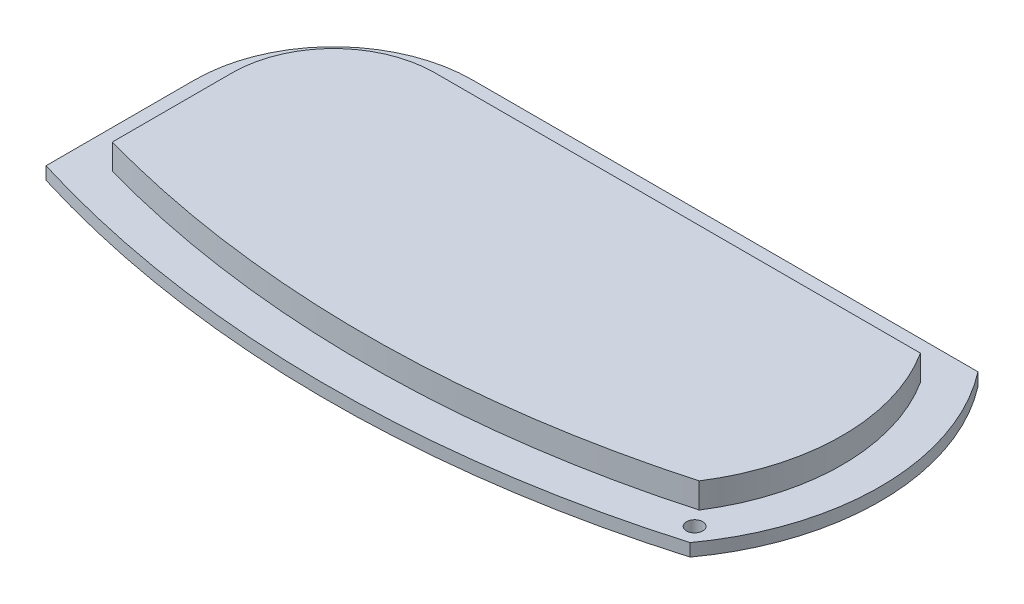
SolidWorks part; units mm, degrees
ref_plane "Front Plane" through (0, 0, 0) normal (0, 0, 1) x (1, 0, 0)
ref_plane "Top Plane" through (0, 0, 0) normal (0, 1, 0) x (1, 0, 0)
ref_plane "Right Plane" through (0, 0, 0) normal (1, 0, 0) x (0, 0, -1)
sketch "Sketch1" plane through (0, 0, 0) normal (0, 1, 0) x (1, 0, 0)
  line L0 (73.7094, 27.7867) -> (-48.3094, 27.7867)
  line L1 (-73.7094, 2.3867) -> (-73.7094, -27.7867)
  arc A0 (-48.3094, 27.7867) -> (-73.7094, 2.3867) centre (-48.3094, 2.3867) ccw
  arc A1 (73.7094, 27.7867) -> (73.7094, -27.7867) centre (30.2858, 0) cw
  arc A2 (-73.7094, -27.7867) -> (73.7094, -27.7867) centre (0, 235.9228) ccw
  point P0 (0, 0)
  point P6 (0, 0)
  dimension "D1" = 25.4
extrude "Extrude1" add sketch "Sketch1" along normal blind 6.35
sketch "Sketch2" plane through (0, 0, 0) normal (0, 1, 0) x (1, 0, 0)
  line L0 (73.7094, 27.7867) -> (-48.3094, 27.7867) construction
  line L1 (73.7094, 27.7867) -> (-48.3094, 27.7867)
  line L2 (-73.7094, 2.3867) -> (-73.7094, -27.7867) construction
  line L3 (-73.7094, 2.3867) -> (-73.7094, -27.7867)
  line L4 (78.6424, 37.3117) -> (-48.3094, 37.3117)
  line L5 (-83.2344, 2.3867) -> (-83.2344, -34.918)
  line L6 (73.7094, 37.3117) -> (-48.3094, 37.3117) construction
  line L9 (-83.2344, 2.3867) -> (-83.2344, -27.7867) construction
  arc A0 (-71.2382, -28.4649) -> (71.2382, -28.4649) centre (0, 235.9228) ccw construction
  arc A1 (-73.7094, -27.7867) -> (73.7094, -27.7867) centre (0, 235.9228) ccw
  arc A3 (-75.107, 25.471) -> (-75.107, -25.471) centre (-30.2858, 0) ccw construction
  arc A4 (75.107, -25.471) -> (75.107, 25.471) centre (30.2858, 0) ccw construction
  arc A5 (73.7094, -27.7867) -> (73.7094, 27.7867) centre (30.2858, 0) ccw
  arc A7 (71.2382, 28.4649) -> (-71.2382, 28.4649) centre (0, -235.9228) ccw construction
  arc A9 (-48.3094, 27.7867) -> (-73.7094, 2.3867) centre (-48.3094, 2.3867) ccw construction
  arc A11 (-71.2382, -28.4649) -> (71.2382, -28.4649) centre (0, 235.9228) ccw construction
  arc A13 (-48.3094, 27.7867) -> (-73.7094, 2.3867) centre (-48.3094, 2.3867) ccw
  arc A15 (75.107, -25.471) -> (75.107, 25.471) centre (30.2858, 0) ccw construction
  arc A16 (-48.3094, 37.3117) -> (-83.2344, 2.3867) centre (-48.3094, 2.3867) ccw
  arc A17 (-83.3882, 30.177) -> (-83.3882, -30.177) centre (-30.2858, 0) ccw construction
  arc A20 (-83.2344, -34.918) -> (79.6262, -36.0007) centre (0, 235.9228) ccw
  arc A21 (83.3882, -30.177) -> (83.3882, 30.177) centre (30.2858, 0) ccw construction
  arc A22 (79.6262, -36.0007) -> (78.6424, 37.3117) centre (30.2858, 0) ccw
  arc A23 (73.7163, 37.6619) -> (-73.7163, 37.6619) centre (0, -235.9228) ccw construction
  arc A24 (73.7163, -37.6619) -> (83.3882, -30.177) centre (69.5862, -22.3336) ccw construction
  arc A25 (-73.7163, -37.6619) -> (73.7163, -37.6619) centre (0, 235.9228) ccw construction
  arc A26 (83.3882, 30.177) -> (73.7163, 37.6619) centre (69.5862, 22.3336) ccw construction
  arc A27 (-73.7163, 37.6619) -> (-83.3882, 30.177) centre (-69.5862, 22.3336) ccw construction
  arc A28 (-83.3882, -30.177) -> (-73.7163, -37.6619) centre (-69.5862, -22.3336) ccw construction
  arc A29 (71.2382, -28.4649) -> (75.107, -25.471) centre (69.5862, -22.3336) ccw construction
  arc A30 (75.107, 25.471) -> (71.2382, 28.4649) centre (69.5862, 22.3336) ccw construction
  arc A31 (-71.2382, 28.4649) -> (-75.107, 25.471) centre (-69.5862, 22.3336) ccw construction
  arc A32 (-75.107, -25.471) -> (-71.2382, -28.4649) centre (-69.5862, -22.3336) ccw construction
  dimension "D1" = 9.525
  dimension "D2" = 9.525
extrude "Extrude2" add sketch "Sketch2" against normal blind 3.175
sketch "Sketch3" plane through (0, 0, 0) normal (0, 1, 0) x (1, 0, 0)
  circle A3 centre (76.6678, -31.8937) radius 2.0317
extrude "Extrude5" cut sketch "Sketch3" against normal blind 3.175
sketch "Sketch6" plane through (0, 0, 0) normal (0, 1, 0) x (1, 0, 0)
  line L2 (78.6424, 37.3117) -> (-48.3094, 37.3117) construction
  line L3 (78.6424, 32.5492) -> (-48.3094, 32.5492) construction
  line L4 (78.6424, 37.3117) -> (-48.3094, 37.3117)
  line L5 (-83.2344, 2.3867) -> (-83.2344, -34.918) construction
  line L7 (-83.2344, 2.3867) -> (-83.2344, -34.918)
  line L8 (76.2266, 32.5492) -> (-48.3094, 32.5492)
  line L9 (-78.4719, 2.3867) -> (-78.4719, -31.3629)
  line L10 (-78.4719, 2.3867) -> (-78.4719, -34.918) construction
  arc A0 (79.6262, -36.0007) -> (78.6424, 37.3117) centre (30.2858, 0) ccw construction
  arc A1 (79.6262, -36.0007) -> (78.6424, 37.3117) centre (30.2858, 0) ccw
  arc A2 (-83.2344, -34.918) -> (79.6262, -36.0007) centre (0, 235.9228) ccw construction
  arc A3 (-83.2344, -34.918) -> (79.6262, -36.0007) centre (0, 235.9228) ccw
  arc A4 (-78.4719, -31.3629) -> (76.6946, -31.8783) centre (0, 235.9228) ccw
  arc A5 (76.6946, -31.8783) -> (76.2266, 32.5492) centre (30.2858, 0) ccw
  arc A7 (-48.3094, 37.3117) -> (-83.2344, 2.3867) centre (-48.3094, 2.3867) ccw construction
  arc A8 (-81.8317, -30.3535) -> (76.6946, -31.8783) centre (0, 235.9228) ccw construction
  arc A9 (76.6946, -31.8783) -> (74.8618, 34.3946) centre (30.2858, 0) ccw construction
  arc A10 (-48.3094, 37.3117) -> (-83.2344, 2.3867) centre (-48.3094, 2.3867) ccw
  arc A11 (-48.3094, 32.5492) -> (-78.4719, 2.3867) centre (-48.3094, 2.3867) ccw
  dimension "D3" = 124.536
  dimension "D1" = 4.7752
  dimension "D2" = 4.7625
